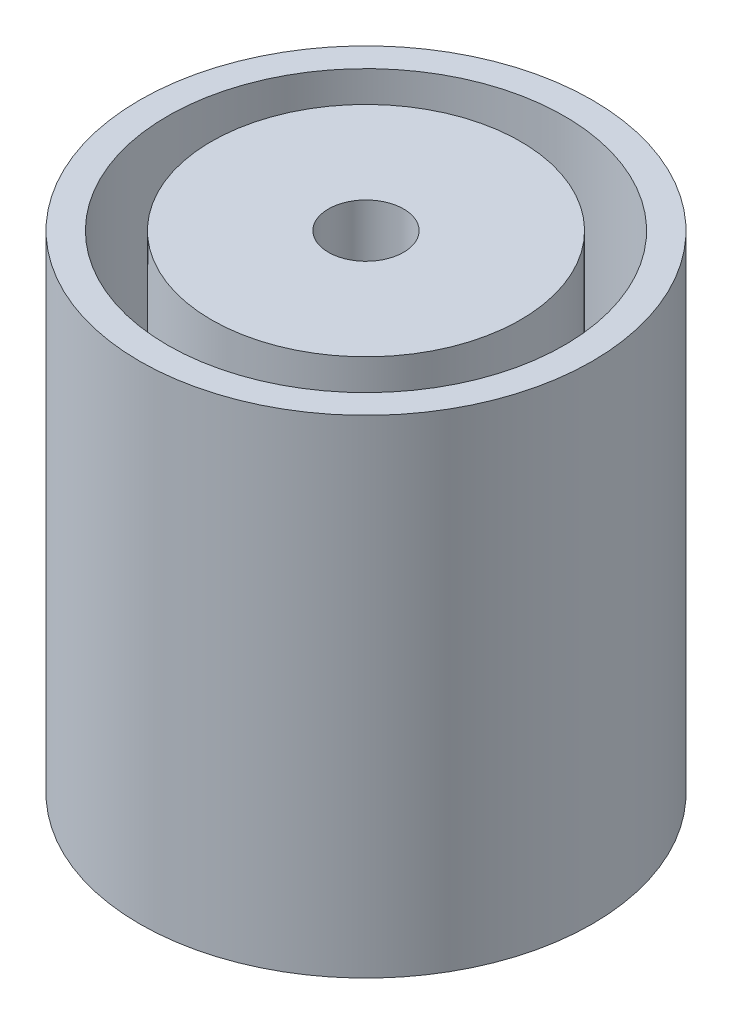
SolidWorks part; units mm, degrees
ref_plane "Front Plane" through (0, 0, 0) normal (0, 0, 1) x (1, 0, 0)
ref_plane "Top Plane" through (0, 0, 0) normal (0, 1, 0) x (1, 0, 0)
ref_plane "Right Plane" through (0, 0, 0) normal (1, 0, 0) x (0, 0, -1)
sketch "Sketch1" plane through (0, 0, 0) normal (0, 1, 0) x (1, 0, 0)
  circle A0 centre (0, 0) radius 16.25
  dimension "D1" = 32.5
extrude "Boss-Extrude1" add sketch "Sketch1" along normal blind 15
sketch "Sketch2" plane through (0, 15, 0) normal (0, 1, 0) x (1, 0, 0)
  circle A0 centre (0, 0) radius 11.1
  dimension "D1" = 22.2
extrude "Boss-Extrude2" add sketch "Sketch2" along normal blind 20
sketch "Sketch3" plane through (0, 15, 0) normal (0, 1, 0) x (1, 0, 0)
  circle A0 centre (0, 0) radius 14.25
  circle A1 centre (0, 0) radius 16.25 construction
  circle A2 centre (0, 0) radius 14.25
  circle M3 centre (0, 0) radius 16.25
  dimension "D1" = 2
  dimension "D2" = 2
extrude "Boss-Extrude4" add sketch "Sketch3" along normal blind 20 contours A0 M3
sketch "Sketch4" plane through (0, 35, 0) normal (0, 1, 0) x (1, 0, 0)
  circle A0 centre (0, 0) radius 2.7
extrude "Cut-Extrude1" cut sketch "Sketch4" against normal blind 30
